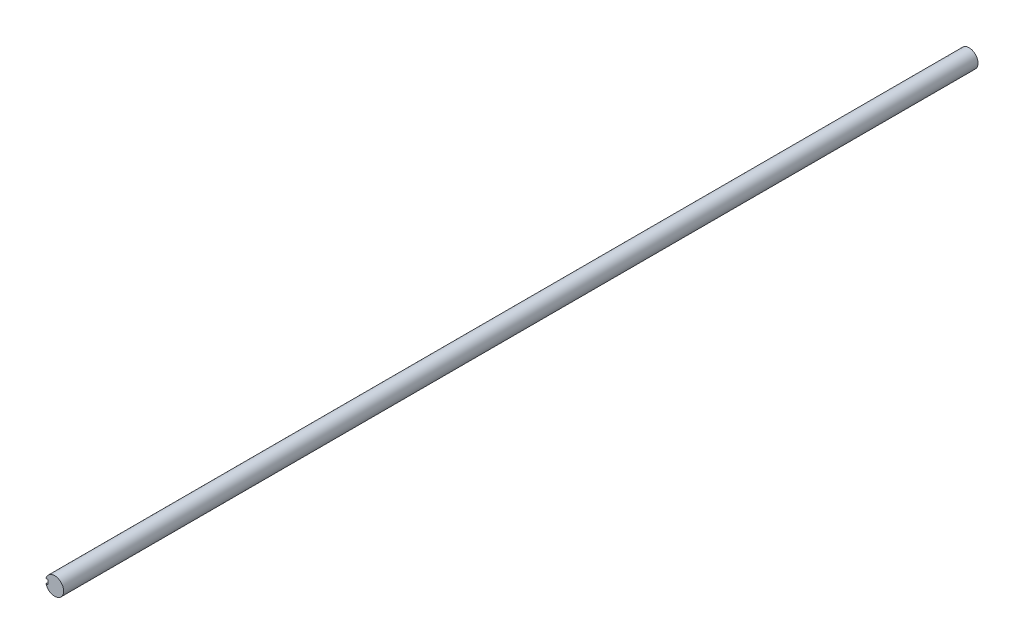
SolidWorks part; units mm, degrees
ref_plane "Front Plane" through (0, 0, 0) normal (0, 0, 1) x (1, 0, 0)
ref_plane "Top Plane" through (0, 0, 0) normal (0, 1, 0) x (1, 0, 0)
ref_plane "Right Plane" through (0, 0, 0) normal (1, 0, 0) x (0, 0, -1)
sketch "Sketch1" plane through (0, 0, 0) normal (0, 0, 1) x (1, 0, 0)
  line L1 (-4.6113, 1.1906) -> (-3.5719, 1.1906)
  line L3 (-4.6113, -1.1906) -> (-3.5719, -1.1906)
  line L4 (-3.5719, 1.1906) -> (-3.5719, -1.1906)
  arc A0 (-4.6113, -1.1906) -> (-4.6113, 1.1906) centre (0, 0) ccw
  point P3 (-4.7625, 0)
  dimension "D1" = 9.525
extrude "Boss-Extrude1" add sketch "Sketch1" along normal blind 486.6957
